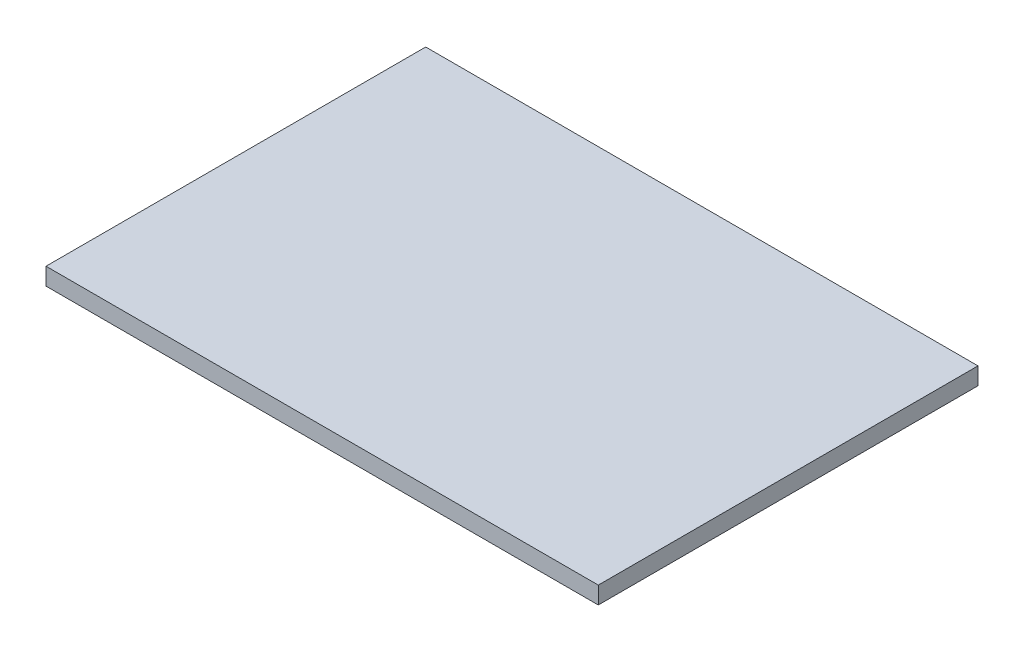
SolidWorks part; units mm, degrees
ref_plane "Front Plane" through (0, 0, 0) normal (0, 0, 1) x (1, 0, 0)
ref_plane "Top Plane" through (0, 0, 0) normal (0, 1, 0) x (1, 0, 0)
ref_plane "Right Plane" through (0, 0, 0) normal (1, 0, 0) x (0, 0, -1)
sketch "Sketch1" plane through (0, 0, 0) normal (0, 1, 0) x (1, 0, 0)
  line L1 (-685.8, -317.5) -> (127, -317.5)
  line L2 (-685.8, -317.5) -> (-685.8, 241.3)
  line L3 (-685.8, 241.3) -> (127, 241.3)
  line L4 (127, -317.5) -> (127, 241.3)
  point P0 (0, 0)
  dimension "D1" = 812.8
  dimension "D2" = 558.8
extrude "Boss-Extrude1" add sketch "Sketch1" along normal blind 25.4
sketch "Sketch3" plane through (0, 25.4, 0) normal (0, 1, 0) x (1, 0, 0)
  line L1 (-685.8, 241.3) -> (-609.6, 241.3)
  line L2 (-685.8, 241.3) -> (-685.8, -317.5)
  line L3 (-685.8, -317.5) -> (-609.6, -317.5)
  line L4 (-609.6, 241.3) -> (-609.6, -317.5)
  dimension "D1" = 76.2
